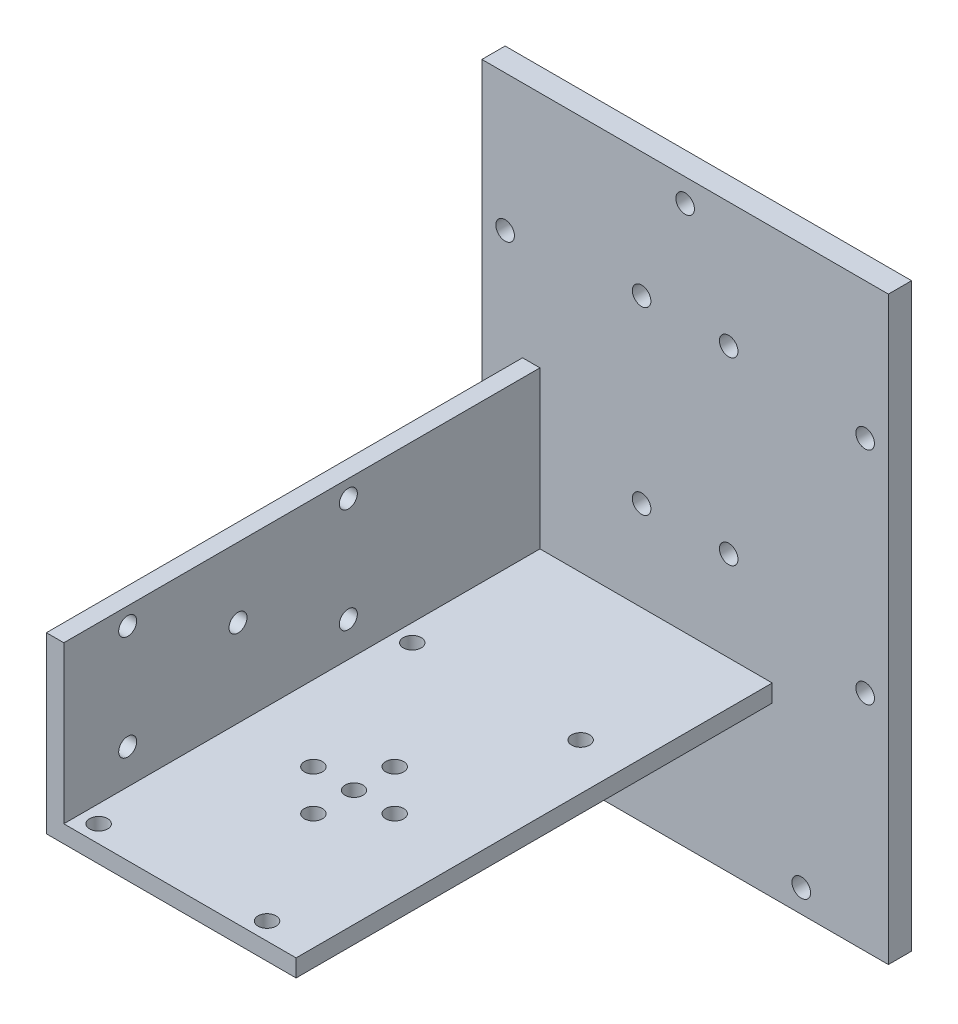
SolidWorks part; units mm, degrees
ref_plane "前视基准面" through (0, 0, 0) normal (0, 0, 1) x (1, 0, 0)
ref_plane "上视基准面" through (0, 0, 0) normal (0, 1, 0) x (1, 0, 0)
ref_plane "右视基准面" through (0, 0, 0) normal (1, 0, 0) x (0, 0, -1)
other "Configuration Table"
sketch "草图1" plane through (0, 0, 0) normal (0, 0, 1) x (1, 0, 0)
  line L0 (0, 0) -> (-16.666, 0) construction
  line L1 (-31.666, 50) -> (38.334, 50)
  line L2 (-31.666, 50) -> (-31.666, -50)
  line L3 (-31.666, -50) -> (38.334, -50)
  line L4 (38.334, 50) -> (38.334, -50)
  line L5 (-16.666, 46) -> (-16.666, -46) construction
  line L6 (-16.666, 46) -> (3.334, 46) construction
  line L7 (10.834, 28.5) -> (10.834, -2.5) construction
  line L8 (3.334, 46) -> (10.834, 46) construction
  line L9 (3.334, 46) -> (3.334, 28.5) construction
  line L10 (3.334, 28.5) -> (10.834, 28.5) construction
  line L11 (10.834, 46) -> (10.834, 28.5) construction
  line L12 (34.334, 26.5) -> (34.334, -11.5) construction
  line L13 (10.834, 28.5) -> (34.334, 28.5) construction
  line L14 (10.834, 28.5) -> (10.834, 26.5) construction
  line L15 (10.834, 26.5) -> (34.334, 26.5) construction
  line L16 (34.334, 28.5) -> (34.334, 26.5) construction
  circle A0 centre (34.334, 26.5) radius 1.6
  circle A1 centre (-16.666, -46) radius 1.6
  circle A2 centre (3.334, 46) radius 1.6
  circle A3 centre (10.834, 28.5) radius 1.6
  circle A4 centre (10.834, -2.5) radius 1.6
  circle A5 centre (34.334, -11.5) radius 1.6
  circle A6 centre (-27.666, 26.5) radius 1.6
  circle A7 centre (-4.166, 28.5) radius 1.6
  circle A8 centre (-4.166, -2.5) radius 1.6
  circle A9 centre (-27.666, -11.5) radius 1.6
  circle A10 centre (23.334, -46) radius 1.6
  point P0 (0, 0)
  point P11 (-16.666, 0)
  point P20 (-31.666, 0)
  dimension "D5" = 15
  dimension "D6" = 3.2
  dimension "D7" = 3.2
  dimension "D8" = 3.2
  dimension "D9" = 3.2
  dimension "D10" = 3.2
  dimension "D11" = 3.2
  dimension "D1" = 100
  dimension "D2" = 70
  dimension "D3" = 92
  dimension "D4" = 20
extrude "凸台-拉伸1" add sketch "草图1" along normal blind 4
sketch "草图2" plane through (0, 0, 4) normal (0, 0, 1) x (1, 0, 0)
  line L0 (3.334, -50) -> (3.334, 50) construction
  line L2 (-31.666, -50) -> (38.334, -50) construction
  line L3 (38.334, 50) -> (-31.666, 50) construction
  line L4 (3.334, -21) -> (18.334, -21)
  line L5 (3.334, -21) -> (-21.666, -21)
  line L7 (-21.666, -21) -> (18.334, -21)
  line L8 (-21.666, -21) -> (-21.666, -18)
  line L9 (-21.666, -18) -> (18.334, -18)
  line L10 (18.334, -21) -> (18.334, -18)
  circle A0 centre (-16.666, -46) radius 1.6 construction
  circle A1 centre (34.334, -11.5) radius 1.6 construction
  circle A2 centre (-16.666, -46) radius 1.6
  circle A3 centre (34.334, -11.5) radius 1.6
  dimension "D1" = 15
  dimension "D2" = 25
  dimension "D3" = 29
  dimension "D4" = 3
extrude "凸台-拉伸2" add sketch "草图2" along normal blind 82 contours L5 L0 L9 L8 | L0 L4 L10 L9
sketch "草图3" plane through (0, -21, 0) normal (0, -1, 0) x (1, 0, 0)
  line L5 (-1.666, 86) -> (-1.666, 27.7683) construction
  line L6 (31.9087, 56) -> (-35.2798, 56) construction
  line L7 (34.6318, 36.4326) -> (34.4725, 36.2733)
  line L8 (-18.666, 83) -> (10.334, 83) construction
  line L9 (-18.666, 83) -> (-18.666, 29) construction
  line L10 (-18.666, 29) -> (10.334, 29) construction
  line L11 (10.334, 83) -> (10.334, 29) construction
  line L12 (18.334, 86) -> (-21.666, 86) construction
  line L14 (18.334, 4) -> (-21.666, 4) construction
  line L19 (18.334, 86) -> (18.334, 4) construction
  line L20 (-21.666, 86) -> (-21.666, 4) construction
  line L21 (18.334, 86) -> (18.334, 4) construction
  line L22 (-21.666, 86) -> (-21.666, 4) construction
  circle A0 centre (-18.666, 83) radius 1.55
  circle A1 centre (10.334, 83) radius 1.55
  circle A2 centre (10.334, 29) radius 1.55
  circle A3 centre (-18.666, 29) radius 1.55
  circle A4 centre (-1.6855, 56) radius 7 construction
  circle A5 centre (-1.6855, 63) radius 1.55
  circle A6 centre (-1.6855, 56) radius 1.5392
  circle A16 centre (5.3145, 56) radius 1.55
  circle A17 centre (-1.6855, 49) radius 1.55
  circle A18 centre (-8.6855, 56) radius 1.55
  point P11 (-1.6855, 56)
  point P30 (13.334, 70)
  point P34 (-4.166, 56)
  point P39 (-1.6855, 56)
  dimension "D3" = 3.1
  dimension "D4" = 14
  dimension "D5" = 3.1
  dimension "D7" = 4
  dimension "D1" = 29
  dimension "D2" = 54
  dimension "D6" = 25
extrude "切除-拉伸1" cut sketch "草图3" against normal blind 8 contours A0 | A1 | A5 | A6 | A18 | A17 | A16 | A3 | A2
sketch "草图5" plane through (0, 0, 4) normal (0, 0, 1) x (1, 0, 0)
  line L0 (-21.666, -18) -> (18.334, -18) construction
  line L1 (-21.666, -18) -> (18.334, -18)
  line L2 (-1.666, -18) -> (-1.666, -5.462)
ref_plane "基准面1" through (-1.666, 0, 0) normal (1, 0, 0) x (0, 1, 0)
sketch "草图6" plane through (-1.666, 0, 0) normal (1, 0, 0) x (0, 1, 0)
  line L1 (-21, 86) -> (-21, 4) construction
  line L4 (-21, 4) -> (-18, 4) construction
  line L5 (-21, 4) -> (-18, 4)
  line L6 (-19.5, 4) -> (-19.5, 59.4681) construction
  line L7 (-21, 44.6174) -> (-35.8733, 4)
  line L8 (-21, 4) -> (-35.8733, 4)
  line L9 (-21, 44.6174) -> (-21, 4)
extrude "凸台-拉伸3" add sketch "草图6" along normal mid plane 4 contours L9 L7 L8
sketch "草图7" plane through (0, 0, 4) normal (0, 0, 1) x (1, 0, 0)
  line L0 (-21.666, -18) -> (18.334, -18) construction
  line L1 (-21.666, -18) -> (18.334, -18)
  line L8 (-21.666, -18) -> (-21.666, 9)
  line L9 (-21.666, 9) -> (-24.666, 9)
  line L10 (-24.666, 9) -> (-24.666, -21)
  line L11 (-24.666, -21) -> (-21.666, -21)
  line L12 (-21.666, -21) -> (-21.666, -18)
  circle M2 centre (-27.666, -11.5) radius 1.6
  line M22 (-21.666, -21) -> (-21.666, -18)
  dimension "D1" = 3
  dimension "D2" = 27
extrude "凸台-拉伸5" add sketch "草图7" along normal blind 82 contours L10 L11 L8 L9 M22 M2
sketch "草图10" plane through (-24.666, 0, 0) normal (1, 0, 0) x (0, 0, -1)
  line L7 (-78.5, -3) -> (-33.5, -3) construction
  line L8 (-78.5, 9) -> (-33.5, 9) construction
  line L9 (-78.5, 9) -> (-78.5, -15) construction
  line L10 (-78.5, -15) -> (-33.5, -15) construction
  line L11 (-33.5, 9) -> (-33.5, -15) construction
  line L12 (-56, -12) -> (-56, 6) construction
  line L17 (-75, -12) -> (-37, 6) construction
  line L18 (-75, 6) -> (-37, -12) construction
  circle A0 centre (-75, -12) radius 1.55
  circle A1 centre (-56, -3) radius 1.55
  circle A2 centre (-75, 6) radius 1.55
  circle A3 centre (-37, 6) radius 1.55
  circle A4 centre (-37, -12) radius 1.55
  point P11 (-56, -3)
  point P23 (-56, -3)
  dimension "D5" = 3.1
  dimension "D6" = 3.1
  dimension "D1" = 24
  dimension "D2" = 45
  dimension "D3" = 18
  dimension "D4" = 38
extrude "切除-拉伸2" cut sketch "草图10" along normal through all contours A2 | A0 | A1 | A3 | A4
